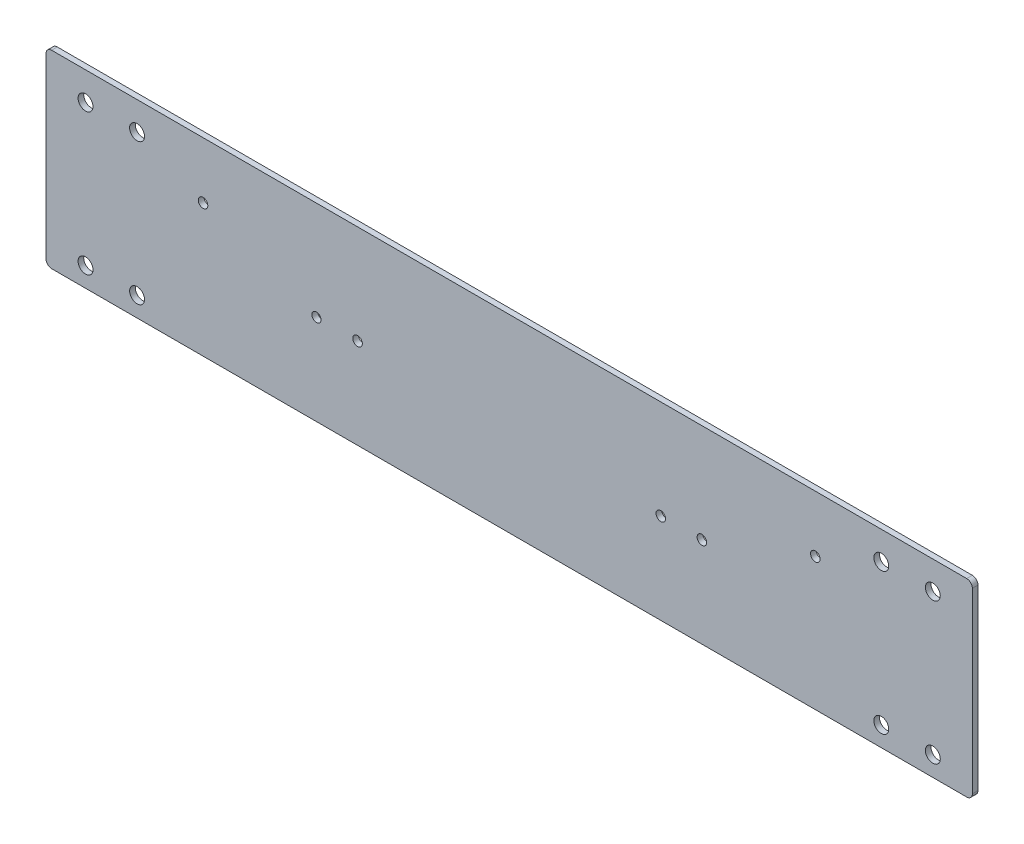
SolidWorks part; units mm, degrees
material "PE High Density"
ref_plane "Front Plane" through (0, 0, 0) normal (0, 0, 1) x (1, 0, 0)
ref_plane "Top Plane" through (0, 0, 0) normal (0, 1, 0) x (1, 0, 0)
ref_plane "Right Plane" through (0, 0, 0) normal (1, 0, 0) x (0, 0, -1)
sketch "Sketch1" plane through (0, 0, 0) normal (0, 0, 1) x (1, 0, 0)
  line L1 (-520.7, 106.3625) -> (520.7, 106.3625)
  line L2 (-520.7, 106.3625) -> (-520.7, -106.3625)
  line L3 (-520.7, -106.3625) -> (520.7, -106.3625)
  line L4 (520.7, 106.3625) -> (520.7, -106.3625)
  line L5 (-520.7, 106.3625) -> (520.7, -106.3625) construction
  line L6 (-520.7, -106.3625) -> (520.7, 106.3625) construction
  circle A3 centre (-216.662, -4.7625) radius 5.1594
  circle A4 centre (-170.434, -4.7625) radius 5.3578
  circle A5 centre (170.434, -4.7625) radius 5.3578
  circle A6 centre (216.662, -4.7625) radius 5.3578
  circle A12 centre (344.17, 42.8625) radius 5.3578
  circle A13 centre (-344.17, 42.8625) radius 5.3578
  point P0 (0, 0)
  dimension "D3" = 10.7156
  dimension "D4" = 10.3187
  dimension "D11" = 10.7156
  dimension "D12" = 10.7156
  dimension "D15" = 63.5
  dimension "D16" = 10.7156
  dimension "D17" = 46.228
  dimension "D18" = 304.038
  dimension "D20" = 63.5
  dimension "D21" = 10.7156
  dimension "D1" = 212.725
  dimension "D2" = 1041.4
  dimension "D5" = 176.53
  dimension "D6" = 176.53
  dimension "D7" = 101.6
  dimension "D8" = 101.6
  dimension "D9" = 101.6
  dimension "D10" = 101.6
  dimension "D13" = 304.038
  dimension "D14" = 46.228
extrude "Boss-Extrude1" add sketch "Sketch1" along normal blind 6.35 contours L2 L1 L4 L3
sketch "Sketch4" plane through (0, 0, 6.35) normal (0, 0, 1) x (1, 0, 0)
  line L2 (-520.7, 106.3625) -> (-520.7, -106.3625) construction
  line L5 (-520.7, -106.3625) -> (520.7, -106.3625) construction
  line L6 (520.7, 106.3625) -> (520.7, -106.3625) construction
  line L7 (-520.7, 106.3625) -> (520.7, 106.3625) construction
  circle A0 centre (476.25, 74.6125) radius 8.382
  circle A1 centre (418.3103, 74.6125) radius 8.382
  circle A2 centre (-476.25, 74.6125) radius 8.382
  circle A3 centre (-418.338, 74.6125) radius 8.382
  circle A4 centre (476.25, -84.1375) radius 8.382
  circle A5 centre (418.3103, -84.1375) radius 8.382
  circle A6 centre (-476.25, -84.1375) radius 8.382
  circle A7 centre (-418.3103, -84.1375) radius 8.382
  dimension "D2" = 16.764
  dimension "D3" = 16.764
  dimension "D4" = 16.764
  dimension "D5" = 16.764
  dimension "D6" = 16.764
  dimension "D7" = 16.764
  dimension "D8" = 16.764
  dimension "D9" = 16.764
  dimension "D1" = 102.362
  dimension "D10" = 22.225
  dimension "D11" = 44.45
  dimension "D12" = 102.3897
  dimension "D13" = 44.45
  dimension "D14" = 102.3897
  dimension "D15" = 22.225
  dimension "D16" = 44.45
  dimension "D17" = 102.3897
  dimension "D18" = 31.75
  dimension "D19" = 44.45
  dimension "D20" = 31.75
extrude "Cut-Extrude1" cut sketch "Sketch4" against normal through all
sketch "Sketch5" plane through (0, 0, 6.35) normal (0, 0, 1) x (1, 0, 0)
  line L0 (-520.7, 106.3625) -> (-520.7, -106.3625) construction
  line L1 (520.7, 106.3625) -> (520.7, -106.3625) construction
  line L2 (-520.7, 106.3625) -> (520.7, 106.3625) construction
  circle A0 centre (-216.662, -4.7625) radius 5.1594
  circle A1 centre (-170.434, -4.7625) radius 5.3578
  circle A2 centre (170.434, -4.7625) radius 5.3578
  circle A3 centre (216.662, -4.7625) radius 5.3578
  circle A4 centre (344.17, 42.8625) radius 5.3578
  circle A5 centre (-344.17, 42.8625) radius 5.3578
  dimension "D1" = 176.53
  dimension "D2" = 176.53
  dimension "D3" = 63.5
  dimension "D4" = 63.5
extrude "Cut-Extrude2" cut sketch "Sketch5" against normal through all
fillet "Fillet1" radius 6.35 4 edges at (520.7, 106.3625, 3.175) (520.7, -106.3625, 3.175) (-520.7, -106.3625, 3.175) (-520.7, 106.3625, 3.175)
